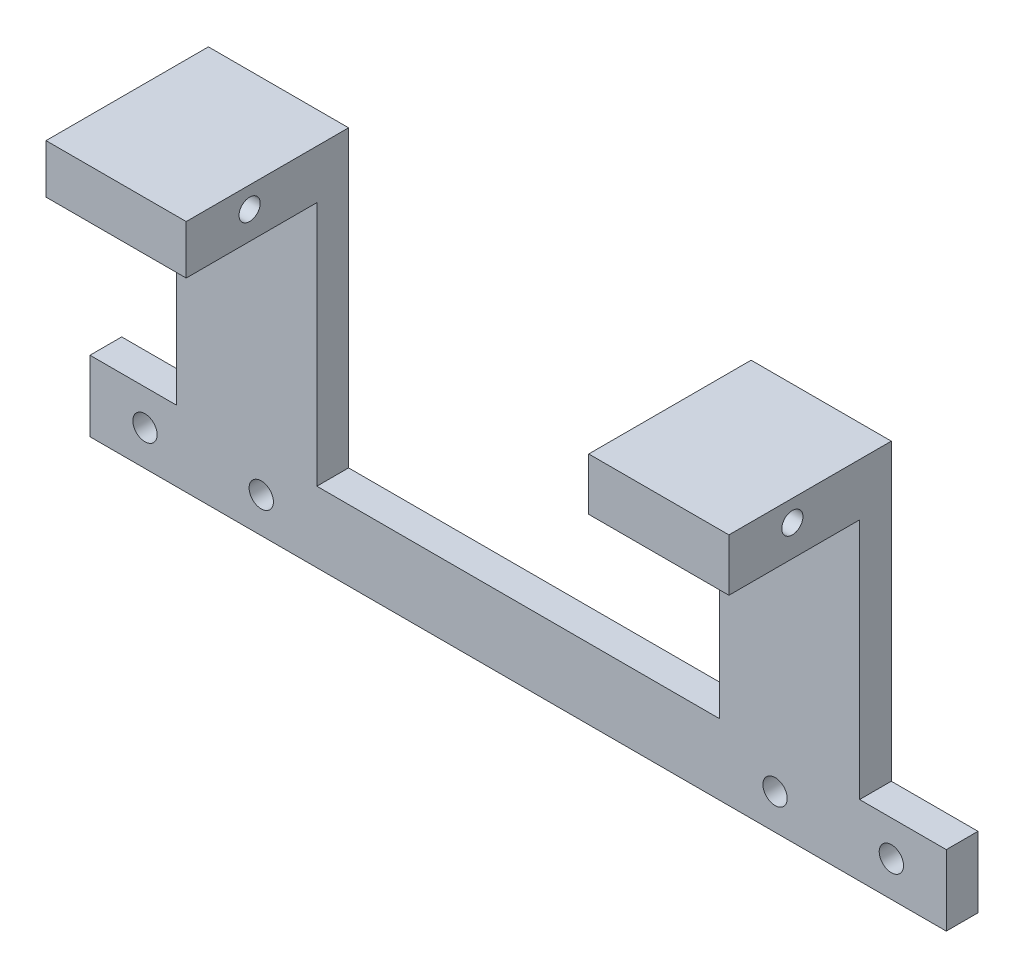
SolidWorks part; units mm, degrees
ref_plane "前视基准面" through (0, 0, 0) normal (0, 0, 1) x (1, 0, 0)
ref_plane "上视基准面" through (0, 0, 0) normal (0, 1, 0) x (1, 0, 0)
ref_plane "右视基准面" through (0, 0, 0) normal (1, 0, 0) x (0, 0, -1)
sketch "草图1" plane through (0, 0, 0) normal (0, 0, 1) x (1, 0, 0)
  line L0 (-32.3006, -10.4326) -> (-32.3006, 17.4274)
  line L1 (-32.3006, 17.4274) -> (-19.0406, 17.4274)
  line L2 (-19.0406, 17.4274) -> (-19.0406, -10.4326)
  line L3 (-19.0406, -10.4326) -> (19.0334, -10.4326)
  line L4 (19.0334, -10.4326) -> (19.0334, 17.4274)
  line L5 (19.0334, 17.4274) -> (32.2934, 17.4274)
  line L6 (32.2934, 17.4274) -> (32.2934, -10.4326)
  line L7 (32.2934, -10.4326) -> (40.4934, -10.4326)
  line L8 (40.4934, -10.4326) -> (40.4934, -17.1126)
  line L9 (40.4934, -17.1126) -> (-40.5006, -17.1126)
  line L10 (-40.5006, -17.1126) -> (-40.5006, -10.4326)
  line L11 (-40.5006, -10.4326) -> (-32.3006, -10.4326)
  line L12 (-35.3006, -13.7726) -> (-24.3006, -13.7726) construction
  line L13 (-24.3006, -13.7726) -> (24.2994, -13.7726) construction
  line L14 (24.2994, -13.7726) -> (35.2994, -13.7726) construction
  line L15 (35.2994, -13.7726) -> (35.2994, -10.4326) construction
  line L16 (35.2994, -13.7726) -> (35.2994, -17.1126) construction
  circle A4 centre (-35.3006, -13.7726) radius 1.15
  circle A5 centre (-24.3006, -13.7726) radius 1.15
  circle A6 centre (24.2994, -13.7726) radius 1.15
  circle A7 centre (35.2994, -13.7726) radius 1.15
  dimension "D1" = 48.6
  dimension "D2" = 11
  dimension "D3" = 38.074
  dimension "D6" = 27.86
  dimension "D7" = 8.2
  dimension "D8" = 6.68
extrude "凸台-拉伸1" add sketch "草图1" along normal blind 3
sketch "草图2" plane through (0, 0, 3) normal (0, 0, 1) x (1, 0, 0)
  line L0 (-19.0406, -10.4326) -> (-19.0406, 17.4274) construction
  line L1 (-32.3006, 17.4274) -> (-19.0406, 17.4274)
  line L2 (-32.3006, 17.4274) -> (-32.3006, 12.7974)
  line L3 (-32.3006, 12.7974) -> (-19.0406, 12.7974)
  line L4 (-19.0406, 17.4274) -> (-19.0406, 12.7974)
  line L5 (32.2934, -10.4326) -> (32.2934, 17.4274) construction
  line L6 (19.0334, 17.4274) -> (32.2934, 17.4274)
  line L7 (19.0334, 17.4274) -> (19.0334, 12.4795)
  line L8 (19.0334, 12.4795) -> (32.2934, 12.4795)
  line L9 (32.2934, 17.4274) -> (32.2934, 12.4795)
  dimension "D1" = 4.63
extrude "凸台-拉伸2" add sketch "草图2" along normal blind 12.36
sketch "草图3" plane through (-32.3006, 0, 0) normal (-1, 0, 0) x (0, 0, 1)
  line L0 (15.36, 15.4274) -> (9.36, 15.4274) construction
  line L1 (15.36, 17.4274) -> (15.36, 12.7974) construction
  line L2 (15.36, 17.4274) -> (0, 17.4274) construction
  circle A0 centre (9.36, 15.4274) radius 1
  dimension "D1" = 2
  dimension "D2" = 6
extrude "切除-拉伸1" cut sketch "草图3" against normal blind 100
